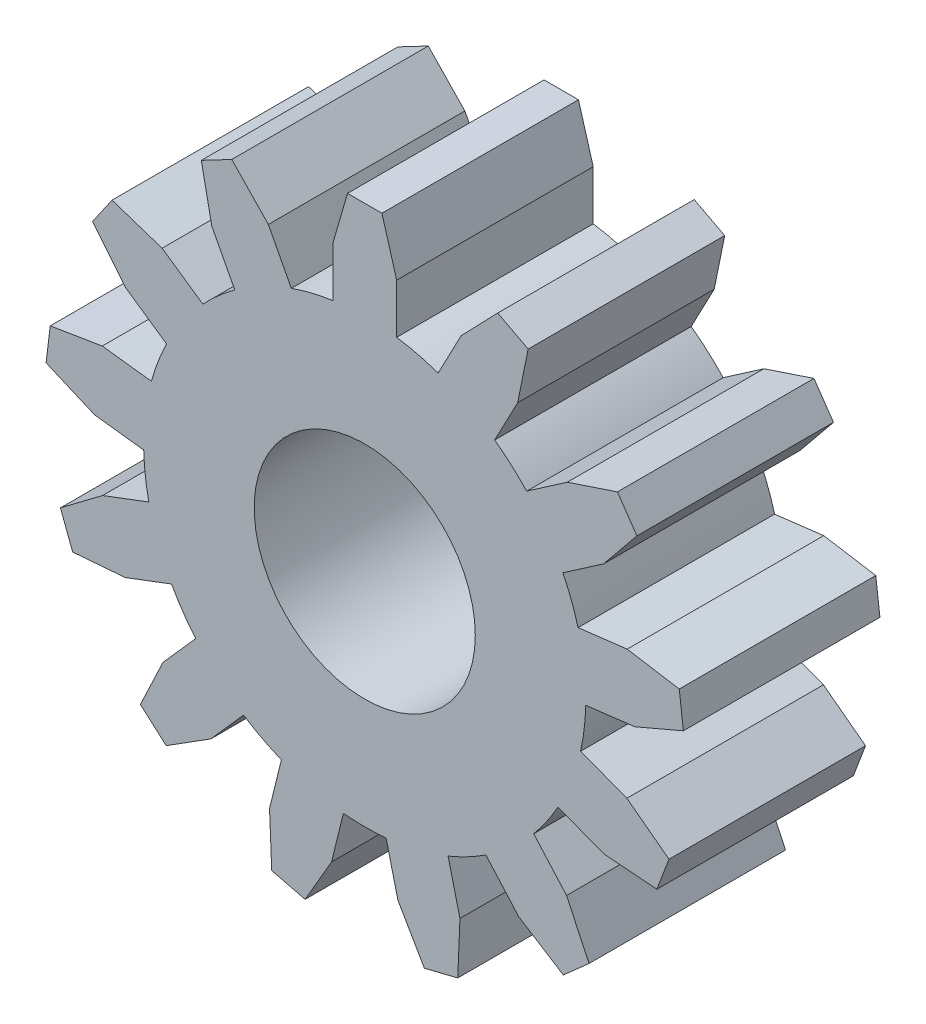
SolidWorks part; units mm, degrees
ref_plane "Płaszczyzna przednia" through (0, 0, 0) normal (0, 0, 1) x (1, 0, 0)
ref_plane "Płaszczyzna górna" through (0, 0, 0) normal (0, 1, 0) x (1, 0, 0)
ref_plane "Płaszczyzna prawa" through (0, 0, 0) normal (1, 0, 0) x (0, 0, -1)
sketch "Szkic1" plane through (0, 0, 0) normal (0, 0, 1) x (1, 0, 0)
  line L0 (-0.65, 5.4601) -> (-0.65, 4.4528)
  line L2 (0.65, 4.4528) -> (0.65, 5.4601)
  line L4 (-0.65, 5.4601) -> (-0.35, 6.4906)
  line L5 (0.65, 5.4601) -> (0.35, 6.4906)
  line L6 (-0.35, 6.4906) -> (0.35, 6.4906)
  line L7 (1.9619, 5.1368) -> (1.4938, 4.2448)
  line L8 (1.9619, 5.1368) -> (2.7064, 5.9098)
  line L9 (2.7064, 5.9098) -> (3.3262, 5.5845)
  line L10 (3.113, 4.5326) -> (3.3262, 5.5845)
  line L11 (2.6449, 3.6407) -> (3.113, 4.5326)
  line L12 (4.1243, 3.6366) -> (3.2953, 3.0644)
  line L13 (4.1243, 3.6366) -> (5.1428, 3.9751)
  line L14 (5.1428, 3.9751) -> (5.5405, 3.399)
  line L15 (4.8628, 2.5668) -> (5.5405, 3.399)
  line L16 (4.0338, 1.9945) -> (4.8628, 2.5668)
  line L17 (5.342, 1.3034) -> (4.342, 1.182)
  line L18 (5.342, 1.3034) -> (6.4011, 1.1298)
  line L19 (6.4011, 1.1298) -> (6.4854, 0.4349)
  line L20 (5.4987, 0.0129) -> (6.4854, 0.4349)
  line L21 (4.4987, -0.1085) -> (5.4987, 0.0129)
  line L22 (5.3358, -1.3284) -> (4.3939, -0.9712)
  line L23 (5.3358, -1.3284) -> (6.1929, -1.9743)
  line L24 (6.1929, -1.9743) -> (5.9447, -2.6288)
  line L25 (4.8748, -2.5439) -> (5.9447, -2.6288)
  line L26 (3.933, -2.1867) -> (4.8748, -2.5439)
  line L27 (4.1073, -3.6559) -> (3.4393, -2.9019)
  line L28 (4.1073, -3.6559) -> (4.566, -4.6262)
  line L29 (4.566, -4.6262) -> (4.0421, -5.0904)
  line L30 (3.1342, -4.518) -> (4.0421, -5.0904)
  line L31 (2.4662, -3.764) -> (3.1342, -4.518)
  line L32 (1.9378, -5.1459) -> (1.6967, -4.1679)
  line L33 (1.9378, -5.1459) -> (1.8931, -6.2182)
  line L34 (1.8931, -6.2182) -> (1.2135, -6.3857)
  line L35 (0.6756, -5.457) -> (1.2135, -6.3857)
  line L36 (0.4345, -4.479) -> (0.6756, -5.457)
  line L37 (-0.6756, -5.457) -> (-0.4345, -4.479)
  line L38 (-0.6756, -5.457) -> (-1.2135, -6.3857)
  line L39 (-1.2135, -6.3857) -> (-1.8931, -6.2182)
  line L40 (-1.9378, -5.1459) -> (-1.8931, -6.2182)
  line L41 (-1.6967, -4.1679) -> (-1.9378, -5.1459)
  line L42 (-3.1342, -4.518) -> (-2.4662, -3.764)
  line L43 (-3.1342, -4.518) -> (-4.0421, -5.0904)
  line L44 (-4.0421, -5.0904) -> (-4.566, -4.6262)
  line L45 (-4.1073, -3.6559) -> (-4.566, -4.6262)
  line L46 (-3.4393, -2.9019) -> (-4.1073, -3.6559)
  line L47 (-4.8748, -2.5439) -> (-3.933, -2.1867)
  line L48 (-4.8748, -2.5439) -> (-5.9447, -2.6288)
  line L49 (-5.9447, -2.6288) -> (-6.1929, -1.9743)
  line L50 (-5.3358, -1.3284) -> (-6.1929, -1.9743)
  line L51 (-4.3939, -0.9712) -> (-5.3358, -1.3284)
  line L52 (-5.4987, 0.0129) -> (-4.4987, -0.1085)
  line L53 (-5.4987, 0.0129) -> (-6.4854, 0.4349)
  line L54 (-6.4854, 0.4349) -> (-6.4011, 1.1298)
  line L55 (-5.342, 1.3034) -> (-6.4011, 1.1298)
  line L56 (-4.342, 1.182) -> (-5.342, 1.3034)
  line L57 (-4.8628, 2.5668) -> (-4.0338, 1.9945)
  line L58 (-4.8628, 2.5668) -> (-5.5405, 3.399)
  line L59 (-5.5405, 3.399) -> (-5.1428, 3.9751)
  line L60 (-4.1243, 3.6366) -> (-5.1428, 3.9751)
  line L61 (-3.2953, 3.0644) -> (-4.1243, 3.6366)
  line L62 (-3.113, 4.5326) -> (-2.6449, 3.6407)
  line L63 (-3.113, 4.5326) -> (-3.3262, 5.5845)
  line L64 (-3.3262, 5.5845) -> (-2.7064, 5.9098)
  line L65 (-1.9619, 5.1368) -> (-2.7064, 5.9098)
  line L66 (-1.4938, 4.2448) -> (-1.9619, 5.1368)
  arc A1 (-0.65, 4.4528) -> (-1.4938, 4.2448) centre (0, 0) ccw
  arc A3 (-2.6449, 3.6407) -> (-3.2953, 3.0644) centre (0, 0) ccw
  arc A4 (-4.0338, 1.9945) -> (-4.342, 1.182) centre (0, 0) ccw
  arc A5 (-4.4987, -0.1085) -> (-4.3939, -0.9712) centre (0, 0) ccw
  arc A6 (-3.933, -2.1867) -> (-3.4393, -2.9019) centre (0, 0) ccw
  arc A7 (-2.4662, -3.764) -> (-1.6967, -4.1679) centre (0, 0) ccw
  arc A8 (-0.4345, -4.479) -> (0.4345, -4.479) centre (0, 0) ccw
  arc A9 (1.6967, -4.1679) -> (2.4662, -3.764) centre (0, 0) ccw
  arc A10 (3.4393, -2.9019) -> (3.933, -2.1867) centre (0, 0) ccw
  arc A11 (4.3939, -0.9712) -> (4.4987, -0.1085) centre (0, 0) ccw
  arc A12 (4.342, 1.182) -> (4.0338, 1.9945) centre (0, 0) ccw
  arc A13 (3.2953, 3.0644) -> (2.6449, 3.6407) centre (0, 0) ccw
  arc A14 (1.4938, 4.2448) -> (0.65, 4.4528) centre (0, 0) ccw
  circle A15 centre (0, 0) radius 2.25
  point P82 (0, 0)
  dimension "D1" = 13
  dimension "D2" = 1.3
  dimension "D3" = 4.5
extrude "Dodanie-wyciągnięcie1" add sketch "Szkic1" along normal blind 4
